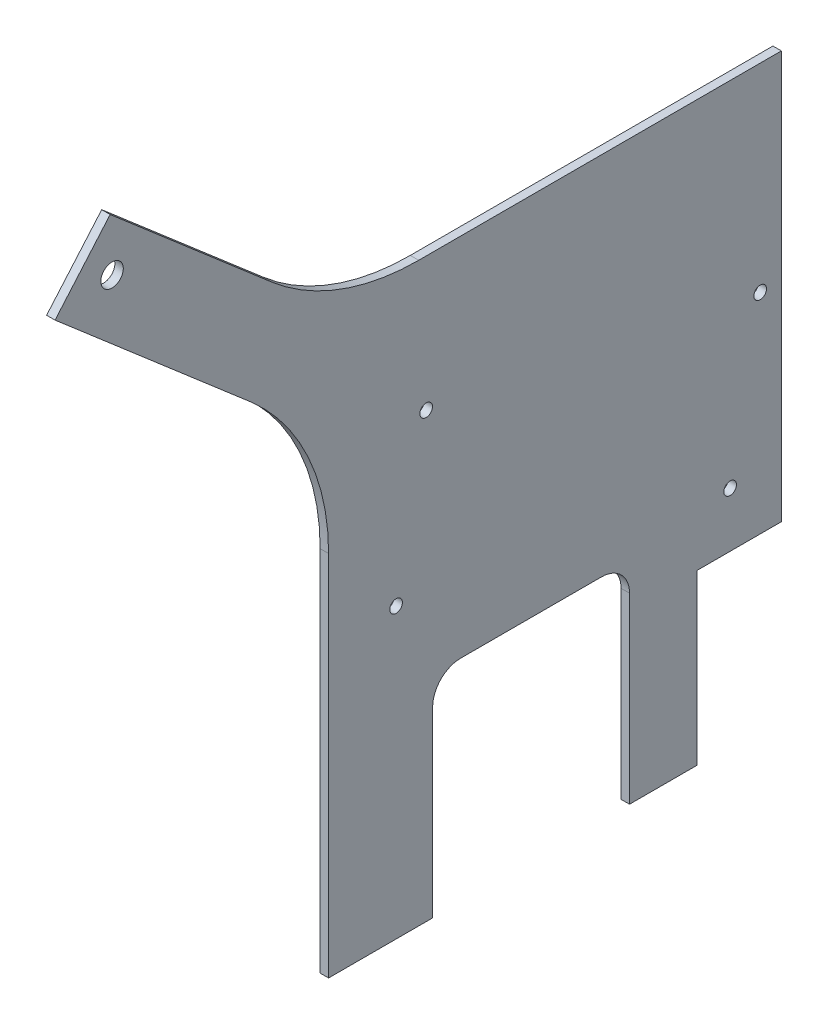
SolidWorks part; units mm, degrees
ref_plane "前视基准面" through (0, 0, 0) normal (0, 0, 1) x (1, 0, 0)
ref_plane "上视基准面" through (0, 0, 0) normal (0, 1, 0) x (1, 0, 0)
ref_plane "右视基准面" through (0, 0, 0) normal (1, 0, 0) x (0, 0, -1)
sketch "草图1" plane through (0, 0, 0) normal (1, 0, 0) x (0, 0, -1)
  line L0 (-27.7697, 191.3174) -> (-97.2699, 251.2218)
  line L1 (0, 0) -> (161, 0)
  line L2 (0, 0) -> (0, 130.7204)
  line L3 (32.0254, 205) -> (161, 205)
  line L4 (161, 0) -> (161, 205)
  line L5 (-97.2699, 251.2218) -> (-77.6836, 273.9456)
  line L6 (-77.6836, 273.9456) -> (-20.2049, 224.403)
  arc A0 (32.0254, 205) -> (-20.2049, 224.403) centre (32.0254, 285) cw
  arc A1 (0, 130.7204) -> (-27.7697, 191.3174) centre (-80, 130.7204) ccw
  circle A2 centre (-77, 255) radius 4
  dimension "D3" = 80
  dimension "D6" = 8
  dimension "D1" = 205
  dimension "D2" = 161
  dimension "D4" = 77
  dimension "D5" = 255
  dimension "D7" = 30
extrude "凸台-拉伸1" add sketch "草图1" along normal mid plane 3
sketch "草图2" plane through (1.5, 0, 0) normal (1, 0, 0) x (0, 0, -1)
  line L0 (0, 0) -> (161, 0) construction
  line L1 (37, 0) -> (107, 0)
  line L2 (37, 0) -> (37, 65)
  line L3 (47, 75) -> (97, 75)
  line L4 (107, 0) -> (107, 65)
  line L5 (0, 130.7204) -> (0, 0) construction
  arc A0 (97, 75) -> (107, 65) centre (97, 65) cw
  arc A1 (47, 75) -> (37, 65) centre (47, 65) ccw
  point P10 (107, 75)
  dimension "D4" = 10
  dimension "D1" = 70
  dimension "D2" = 37
  dimension "D3" = 75
extrude "切除-拉伸1" cut sketch "草图2" against normal through all
hole_wizard "M4 间隙孔1" positions "草图4" profile "草图3" hole size "M4" standard "GB"
sketch "草图4" plane through (1.5, 0, 0) normal (1, 0, 0) x (0, 0, -1)
  line L0 (0, 0) -> (37, 0) construction
  line L1 (0, 130.7204) -> (0, 0) construction
  line L2 (153.4649, 134.4022) -> (142.7749, 79.432) construction
  line L4 (34.69, 157.5002) -> (24, 102.53) construction
  line L6 (24, 102.53) -> (142.7749, 79.432) construction
  point P0 (34.69, 157.5002)
  point P1 (24, 102.53)
  point P3 (153.4649, 134.4022)
  point P5 (142.7749, 79.432)
  dimension "D1" = 56
  dimension "D2" = 102.53
  dimension "D3" = 24
  dimension "D4" = 34.69
  dimension "D5" = 121
sketch "草图3" plane through (1.5, 157.5002, -34.69) normal (0, 1, 0) x (0, 0, -1)
  line L0 (0, 0) -> (0, 5.3519)
  line L1 (0, 5.3519) -> (2.25, 4)
  line L2 (2.25, 4) -> (2.25, 0)
  line L5 (2.25, 0) -> (0, 0)
  line L10 (0, 5.3519) -> (-2.25, 4) construction
  line L11 (0, -6.35) -> (0, 107.95) construction
  dimension "孔直径" = 4.5
  dimension "孔深度" = 4
  dimension "导头角度" = 118
sketch "草图5" plane through (1.5, 0, 0) normal (1, 0, 0) x (0, 0, -1)
  line L1 (161, 0) -> (131, 0)
  line L2 (161, 0) -> (161, 60)
  line L3 (161, 60) -> (131, 60)
  line L4 (131, 0) -> (131, 60)
  dimension "D1" = 30
  dimension "D2" = 60
extrude "切除-拉伸2" cut sketch "草图5" against normal through all
